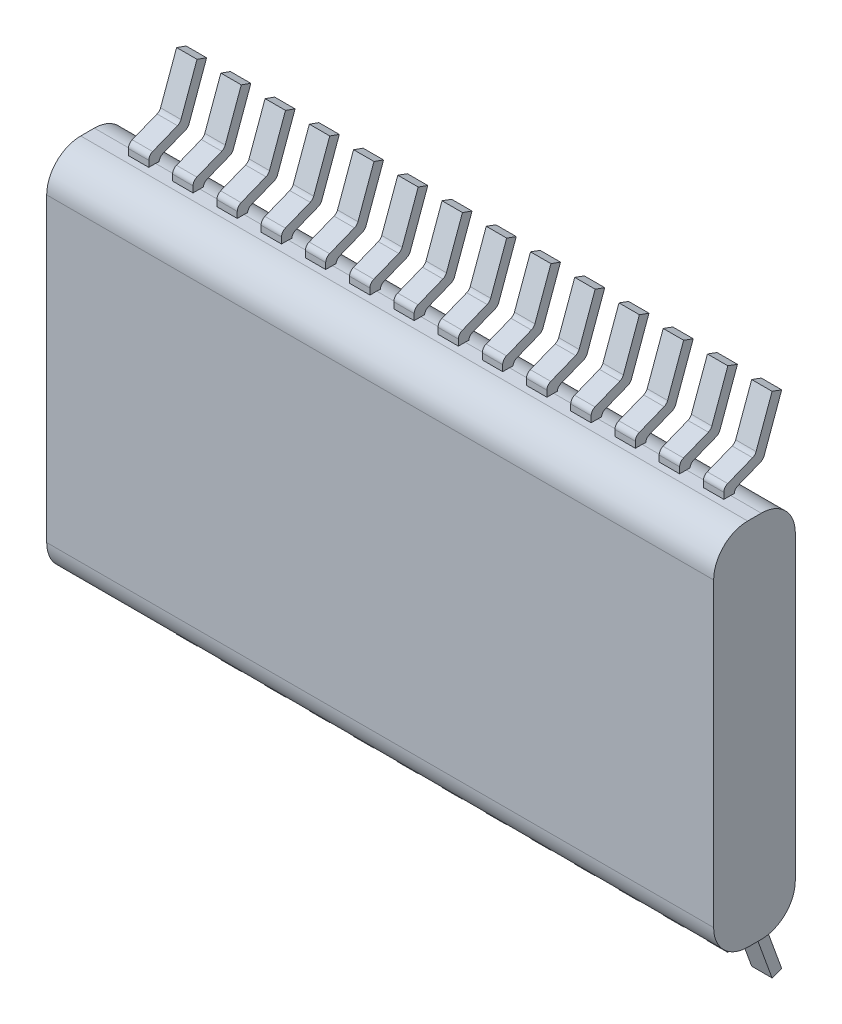
SolidWorks part; units mm, degrees
ref_plane "Front Plane" through (0, 0, 0) normal (0, 0, 1) x (1, 0, 0)
ref_plane "Top Plane" through (0, 0, 0) normal (0, 1, 0) x (1, 0, 0)
ref_plane "Right Plane" through (0, 0, 0) normal (1, 0, 0) x (0, 0, -1)
sketch "Sketch1" plane through (0, 0, 0) normal (0, 0, 1) x (1, 0, 0)
  line L1 (0, 0) -> (9.8, 0)
  line L2 (0, 0) -> (0, 5.4238)
  line L3 (0, 5.4238) -> (9.8, 5.4238)
  line L4 (9.8, 0) -> (9.8, 5.4238)
  dimension "D1" = 9.8
  dimension "D2" = 5.4238
extrude "Boss-Extrude1" add sketch "Sketch1" along normal blind 1.2
fillet "Fillet1" radius 0.5 4 edges at (4.9, 5.4238, 1.2) (4.9, 5.4238, 0) (4.9, 0, 0) (4.9, 0, 1.2)
sketch "Sketch2" plane through (9.8, 0, 0) normal (1, 0, 0) x (0, 0, -1)
  line L0 (-0.6, 0) -> (-0.6, -0.0898)
  line L1 (-0.7, 0) -> (-0.5, 0) construction
  line L2 (-0.5433, -0.1734) -> (-0.1779, -0.3191)
  line L3 (-0.1267, -0.372) -> (0.109, -1.0209)
  line L4 (0.109, -1.0209) -> (0.25, -0.9697)
  line L5 (0.25, -0.9697) -> (-0.0086, -0.2576)
  line L6 (-0.0599, -0.2047) -> (-0.3915, -0.0725)
  line L7 (-0.3915, -0.0725) -> (-0.45, -0.0491) construction
  line L8 (0, 0.5) -> (0, 4.9238) construction
  line L9 (-0.6, -0.0491) -> (-0.45, -0.0491) construction
  line L10 (-0.3387, -0.255) -> (-0.2832, -0.1157) construction
  line L11 (-1.2, 2.7119) -> (0, 2.7119) construction
  line L12 (-1.2, 0.5) -> (-1.2, 4.9238) construction
  line L13 (-0.6, 0) -> (-0.5, 0)
  line L14 (-0.3387, 5.6788) -> (-0.2832, 5.5395) construction
  line L15 (-0.6, 5.473) -> (-0.45, 5.473) construction
  line L16 (-0.3915, 5.4963) -> (-0.45, 5.473) construction
  line L17 (-0.6, 5.4238) -> (-0.5, 5.4238)
  line L18 (-0.0599, 5.6285) -> (-0.3915, 5.4963)
  line L19 (0.25, 6.3935) -> (-0.0086, 5.6814)
  line L20 (0.109, 6.4447) -> (0.25, 6.3935)
  line L21 (-0.1267, 5.7958) -> (0.109, 6.4447)
  line L22 (-0.5433, 5.5972) -> (-0.1779, 5.743)
  line L23 (-0.6, 5.4238) -> (-0.6, 5.5136)
  arc A0 (-0.5, 0) -> (0, 0.5) centre (-0.5, 0.5) ccw construction
  arc A1 (-0.1779, -0.3191) -> (-0.1267, -0.372) centre (-0.2113, -0.4027) cw
  arc A2 (-0.0086, -0.2576) -> (-0.0599, -0.2047) centre (-0.0932, -0.2883) ccw
  arc A3 (-0.3915, -0.0725) -> (-0.4477, 0.0027) centre (-0.3581, 0.0111) cw
  arc A4 (-0.6, -0.0898) -> (-0.5433, -0.1734) centre (-0.51, -0.0898) ccw
  arc A5 (-0.5, 0) -> (-0.4477, 0.0027) centre (-0.5, 0.5) ccw
  arc A6 (-0.5, 5.4238) -> (-0.4477, 5.4211) centre (-0.5, 4.9238) cw
  arc A7 (-0.6, 5.5136) -> (-0.5433, 5.5972) centre (-0.51, 5.5136) cw
  arc A8 (-0.3915, 5.4963) -> (-0.4477, 5.4211) centre (-0.3581, 5.4127) ccw
  arc A9 (-0.0086, 5.6814) -> (-0.0599, 5.6285) centre (-0.0932, 5.7121) cw
  arc A10 (-0.1779, 5.743) -> (-0.1267, 5.7958) centre (-0.2113, 5.8266) ccw
  point P26 (-0.0224, -0.2197)
  point P51 (-0.0224, 5.6435)
  dimension "D4" = 0.09
  dimension "D1" = 0.25
  dimension "D2" = 0.15
  dimension "D3" = 0.75
  dimension "D5" = 0.0898
extrude "Boss-Extrude2" add sketch "Sketch2" against normal blind 0.3 from offset 0.45 separate body offset against normal yes
pattern_linear "LPattern1" count 14 spacing 0.65 along (-1, 0, 0) of "Boss-Extrude2"
